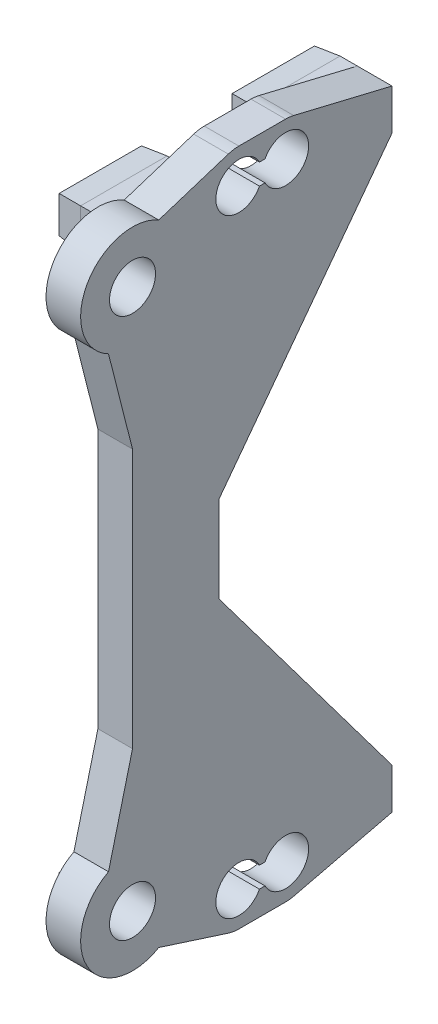
SolidWorks part; units mm, degrees
ref_plane "Front Plane" through (0, 0, 0) normal (0, 0, 1) x (1, 0, 0)
ref_plane "Top Plane" through (0, 0, 0) normal (0, 1, 0) x (1, 0, 0)
ref_plane "Right Plane" through (0, 0, 0) normal (1, 0, 0) x (0, 0, -1)
sketch "SlideGeometry"
  dimension "D1" = 50.8
  dimension "D2" = 12.7
  dimension "D3" = 38.1
  dimension "D4" = 63.5
  dimension "D6" = 12.7
  dimension "D7" = 6.35
  dimension "D8" = 6.35
  dimension "D9" = 12.7
  dimension "D12" = 3.81
  dimension "D5" = 9.525
  dimension "D10" = 12.7
sketch_block_instance "PulleyOutline-1"
sketch_block "PulleyOutline" parameters "D1"=11.1125, "D2"=13.6525
sketch_block_instance "PulleyOutline-2"
sketch_block_instance "PulleyOutline-3"
sketch_block_instance "PulleyOutline-4"
sketch_block_instance "PulleyOutline-5"
sketch_block_instance "PulleyOutline-6"
sketch_block_instance "SlotOutline-1"
sketch_block "SlotOutline" parameters "D1"=6.35, "D2"=3
sketch_block_instance "SlotOutline-3"
sketch "Sketch3" plane through (0, 0, 0) normal (1, 0, 0) x (0, 0, -1)
  circle A0 centre (-3.175, 19.8438) radius 3.81
  circle A1 centre (-3.175, 19.8438) radius 1.5 construction
  dimension "D1" = 7.62
  dimension "D2" = 3
extrude "DowelSupport" add sketch "Sketch3" along normal mid plane 2.54
sketch "Sketch5" plane through (0, 0, 0) normal (1, 0, 0) x (0, 0, -1)
  line L1 (-3.175, -9.525) -> (3.175, -9.525)
  line L2 (-3.175, -9.525) -> (-3.175, 9.525)
  line L3 (-3.175, 9.525) -> (3.175, 9.525)
  line L4 (3.175, -9.525) -> (3.175, 9.525)
  line L5 (-3.175, -9.525) -> (3.175, 9.525) construction
  line L6 (-3.175, 9.525) -> (3.175, -9.525) construction
  point P0 (0, 0)
  dimension "D2" = 19.05
extrude "SliderDowelSupport" add sketch "Sketch5" along normal mid plane 2.54 separate body contours L3 L4 L1 L2
sketch "Sketch8" plane through (0, 0, 0) normal (1, 0, 0) x (0, 0, -1)
  line L0 (4.6355, 22.352) -> (8.0645, 22.352) construction
  line L1 (4.6355, 24.892) -> (8.0645, 24.892)
  line L2 (4.6355, 19.812) -> (8.0645, 19.812)
  line L3 (6.35, 25.4) -> (-6.35, 25.4) construction
  circle A0 centre (4.6355, 22.352) radius 1.5 construction
  circle A1 centre (8.0645, 22.352) radius 1.5 construction
  arc A2 (4.6355, 24.892) -> (4.6355, 19.812) centre (4.6355, 22.352) ccw
  arc A3 (5.7373, 23.3698) -> (5.5245, 22.352) centre (8.0645, 22.352) ccw construction
  arc A4 (8.0645, 24.892) -> (6.35, 24.2261) centre (8.0645, 22.352) ccw construction
  arc A5 (6.35, 24.2261) -> (4.6355, 24.892) centre (4.6355, 22.352) ccw construction
  arc A6 (6.35, 24.2261) -> (5.7373, 23.3698) centre (8.0645, 22.352) ccw construction
  arc A7 (6.9627, 23.3698) -> (6.35, 24.2261) centre (4.6355, 22.352) ccw construction
  arc A8 (7.1755, 22.352) -> (6.9627, 23.3698) centre (4.6355, 22.352) ccw construction
  arc A9 (6.9627, 21.3342) -> (7.1755, 22.352) centre (4.6355, 22.352) ccw construction
  arc A10 (6.35, 20.4779) -> (6.9627, 21.3342) centre (4.6355, 22.352) ccw construction
  arc A11 (5.7373, 21.3342) -> (6.35, 20.4779) centre (8.0645, 22.352) ccw construction
  arc A12 (8.0645, 19.812) -> (8.0645, 24.892) centre (8.0645, 22.352) ccw
  arc A13 (4.6355, 19.812) -> (6.35, 20.4779) centre (4.6355, 22.352) ccw construction
  arc A14 (6.35, 20.4779) -> (8.0645, 19.812) centre (8.0645, 22.352) ccw construction
  arc A15 (5.5245, 22.352) -> (5.7373, 21.3342) centre (8.0645, 22.352) ccw construction
  point P11 (6.35, 22.352)
  dimension "D1" = 3
  dimension "D3" = 5.08
  dimension "D2" = 3.429
  dimension "D4" = 0.508
  dimension "D5" = 9.525
extrude "StringDowelSupport" add sketch "Sketch8" along normal mid plane 2.54 separate body
sketch "Sketch9" plane through (0, 0, 0) normal (1, 0, 0) x (0, 0, -1)
  line B0 (3.175, 20.09) -> (-3.175, 20.09)
  line B1 (3.175, 20.09) -> (3.175, 23.09)
  line B2 (3.175, 23.09) -> (-3.175, 23.09)
  line B3 (-3.175, 20.09) -> (-3.175, 23.09)
  line B4 (3.175, 20.09) -> (-3.175, 23.09) construction
  line B5 (3.175, 23.09) -> (-3.175, 20.09) construction
  line B6 (15.875, 20.09) -> (9.525, 20.09)
  line B7 (15.875, 20.09) -> (15.875, 23.09)
  line B8 (15.875, 23.09) -> (9.525, 23.09)
  line B9 (9.525, 20.09) -> (9.525, 23.09)
sketch_block_instance "3DPTabGeo-1"
sketch_block "3DPTabGeo" parameters "D1"=3, "D2"=6.35
sketch_block_instance "3DPTabGeo-2"
extrude "TabSupport" add sketch "Sketch9" along normal mid plane 2.54
sketch "Sketch10" plane through (0, 0, 0) normal (1, 0, 0) x (0, 0, -1)
  line L0 (-3.175, 9.525) -> (-5.6368, 19.2185)
  line L1 (-5.6368, 19.2185) -> (-0.7132, 20.469) construction
  line L2 (-3.175, 9.525) -> (3.175, 9.525)
  line L3 (3.175, 9.525) -> (3.175, 3.175)
  line L4 (3.175, 3.175) -> (15.875, 20.09)
  line L5 (15.875, 20.09) -> (15.875, 23.09)
  line L6 (15.875, 23.09) -> (8.6571, 24.8219)
  line L7 (8.6571, 24.8219) -> (3.8589, 24.7704)
  line L8 (3.8589, 24.7704) -> (-3.9516, 22.2621)
  line L9 (-3.9516, 22.2621) -> (-2.3984, 17.4254) construction
  line L10 (-5.6368, 19.2185) -> (-3.9516, 22.2621)
  line L11 (3.175, -9.525) -> (3.175, 9.525) construction
  arc A0 (4.6355, 24.892) -> (4.6355, 19.812) centre (4.6355, 22.352) ccw construction
  arc A1 (8.0645, 19.812) -> (8.0645, 24.892) centre (8.0645, 22.352) ccw construction
  point P3 (-3.175, 19.8438)
  dimension "D1" = 5.08
  dimension "D2" = 6.35
extrude "InterSupport" add sketch "Sketch10" along normal mid plane 2.54
sketch "Sketch11" plane through (0, 0, 0) normal (1, 0, 0) x (0, 0, -1)
  line L1 (6.1445, 21.59) -> (6.5555, 21.59)
  line L2 (6.1445, 21.59) -> (6.1445, 23.114) construction
  line L3 (6.1445, 23.114) -> (6.5555, 23.114)
  line L4 (6.5555, 21.59) -> (6.5555, 23.114) construction
  line L5 (6.1445, 21.59) -> (6.5555, 23.114) construction
  line L6 (6.1445, 23.114) -> (6.5555, 21.59) construction
  circle A0 centre (-3.175, 19.8438) radius 1.6905
  arc A1 (6.1445, 23.114) -> (6.1445, 21.59) centre (4.6355, 22.352) ccw
  arc A2 (6.5555, 21.59) -> (6.5555, 23.114) centre (8.0645, 22.352) ccw
  arc A3 (6.323, 22.452) -> (6.1445, 23.114) centre (4.6355, 22.352) ccw construction
  arc A4 (6.5555, 23.114) -> (6.377, 22.452) centre (8.0645, 22.352) ccw construction
  arc A5 (6.377, 22.452) -> (6.377, 22.252) centre (8.0645, 22.352) ccw construction
  arc A6 (6.323, 22.252) -> (6.323, 22.452) centre (4.6355, 22.352) ccw construction
  arc A7 (6.1445, 21.59) -> (6.323, 22.252) centre (4.6355, 22.352) ccw construction
  arc A8 (6.377, 22.252) -> (6.5555, 21.59) centre (8.0645, 22.352) ccw construction
  point P9 (6.35, 22.352)
  dimension "D1" = 3.381
  dimension "D2" = 3.381
  dimension "D3" = 1.524
extrude "DowelHoles" cut sketch "Sketch11" against normal through all both and the other way through all
sketch "Sketch14" plane through (-1.27, 0, 0) normal (-1, 0, 0) x (0, 0, 1)
  line B0 (-9.525, 20.09) -> (-15.875, 20.09)
  line B1 (-9.525, 20.09) -> (-9.525, 23.09)
  line B2 (-9.525, 23.09) -> (-15.875, 23.09)
  line B3 (-15.875, 20.09) -> (-15.875, 23.09)
  line B4 (-9.525, 23.09) -> (-15.875, 20.09) construction
  line B5 (3.175, 20.09) -> (-3.175, 20.09)
  line B6 (3.175, 20.09) -> (3.175, 23.09)
  line B7 (3.175, 23.09) -> (-3.175, 23.09)
  line B8 (-3.175, 20.09) -> (-3.175, 23.09)
sketch_block_instance "3DPTabGeo-3"
sketch_block_instance "3DPTabGeo-4"
extrude "TabBase" add sketch "Sketch14" along normal blind 1.27
sketch "Sketch15" plane through (-2.54, 0, 0) normal (-1, 0, 0) x (0, 0, 1)
  line L0 (-3.175, 23.09) -> (-3.175, 20.09) construction
  line L1 (-3.175, 20.09) -> (3.175, 20.09) construction
  line L2 (3.175, 20.09) -> (3.175, 23.09) construction
  line L3 (3.175, 23.09) -> (-3.175, 23.09) construction
  line L4 (-15.875, 23.09) -> (-15.875, 20.09) construction
  line L5 (-15.875, 20.09) -> (-9.525, 20.09) construction
  line L6 (-9.525, 20.09) -> (-9.525, 23.09) construction
  line L7 (-9.525, 23.09) -> (-15.875, 23.09) construction
  line L8 (-3.175, 23.09) -> (-3.175, 20.09)
  line L9 (-3.175, 20.09) -> (3.175, 20.09)
  line L10 (3.175, 20.09) -> (3.175, 23.09)
  line L11 (3.175, 23.09) -> (-3.175, 23.09)
  line L12 (-15.875, 23.09) -> (-15.875, 20.09)
  line L13 (-15.875, 20.09) -> (-9.525, 20.09)
  line L14 (-9.525, 20.09) -> (-9.525, 23.09)
  line L15 (-9.525, 23.09) -> (-15.875, 23.09)
extrude "TabDraft" add sketch "Sketch15" along normal offset from surface 3 draft 5
mirror "Mirror1" about plane through (0, 0, 0) normal (0, 1, 0) of bodies 118 115
equation "\"StageWidth\"= 2in"
equation "\"D1@SlideGeometry\" = \"StageWidth\""
equation "\"StageOffset\"= .5in"
equation "\"D3@SlideGeometry\" = \"StageWidth\" - \"StageOffset\""
equation "\"D4@SlideGeometry\" = \"StageWidth\" + \"StageOffset\""
equation "\"SlideOffset\"= 0.5in"
equation "\"D6@SlideGeometry\" = \"SlideOffset\""
equation "\"D7@SlideGeometry\" = \"StageOffset\" / 2"
equation "\"D8@SlideGeometry\" = \"StageOffset\" / 2"
equation "\"D9@SlideGeometry\" = \"SlideOffset\""
equation "\"OuterThickness\"= 0.1in"
equation "\"D1@SliderDowelSupport\"=\"OuterThickness\""
equation "\"D1@DowelSupport\"=\"OuterThickness\""
equation "\"DowelClearance\"= 3mm + .015in"
equation "\"D1@TabSupport\" = \"OuterThickness\""
equation "\"D1@InterSupport\" = \"OuterThickness\""
equation "\"D1@Sketch11\"=\"DowelClearance\""
equation "\"D2@Sketch11\"=\"DowelClearance\""
equation "\"SliderDowelLength\"= .5in"
equation "\"D2@Sketch5\"=\"SliderDowelLength\"+.25in"
